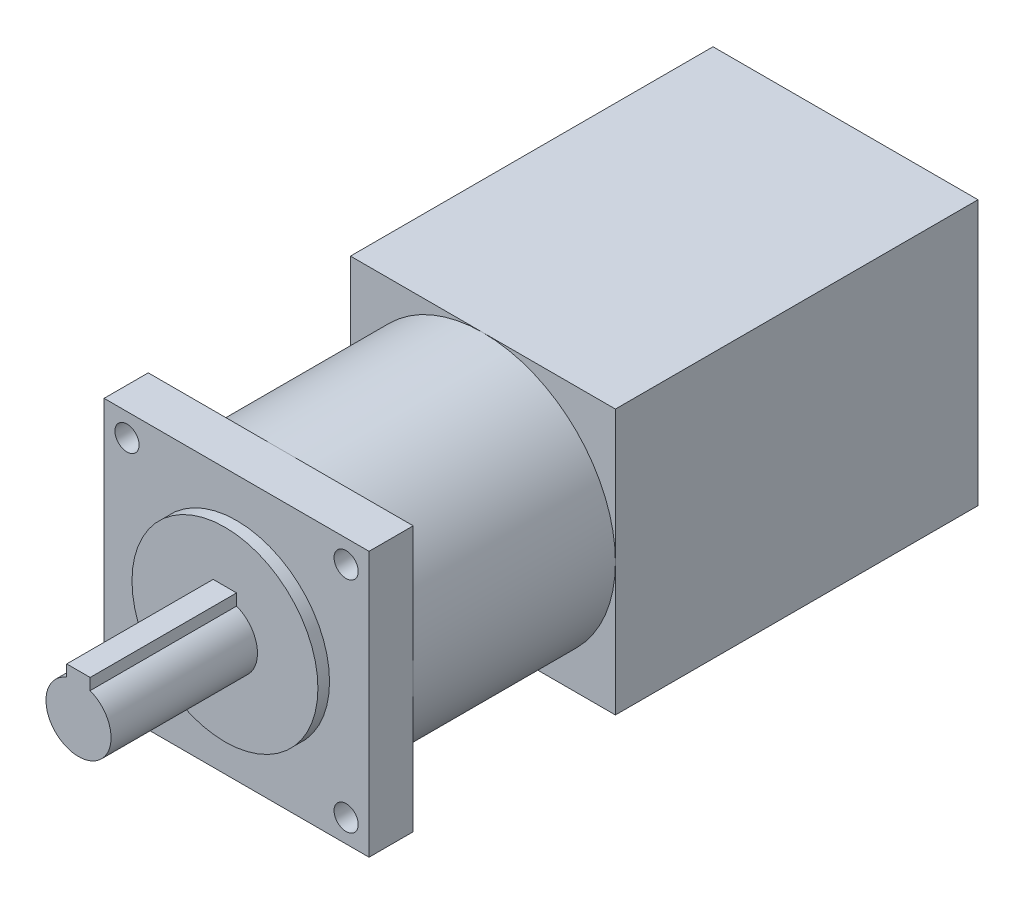
SolidWorks part; units mm, degrees
ref_plane "前视基准面" through (0, 0, 0) normal (0, 0, 1) x (1, 0, 0)
ref_plane "上视基准面" through (0, 0, 0) normal (0, 1, 0) x (1, 0, 0)
ref_plane "右视基准面" through (0, 0, 0) normal (1, 0, 0) x (0, 0, -1)
sketch "草图1" plane through (0, 0, 0) normal (0, 0, 1) x (1, 0, 0)
  line L1 (-28.5, 28.5) -> (28.5, 28.5)
  line L2 (-28.5, 28.5) -> (-28.5, -28.5)
  line L3 (-28.5, -28.5) -> (28.5, -28.5)
  line L4 (28.5, 28.5) -> (28.5, -28.5)
  line L5 (-28.5, 28.5) -> (28.5, -28.5) construction
  line L6 (-28.5, -28.5) -> (28.5, 28.5) construction
  point P0 (0, 0)
  dimension "D1" = 57
extrude "凸台-拉伸1" add sketch "草图1" along normal blind 78
sketch "草图2" plane through (0, 0, 78) normal (0, 0, 1) x (1, 0, 0)
  circle A0 centre (0, 0) radius 28.5
  dimension "D1" = 57
extrude "凸台-拉伸2" add sketch "草图2" along normal blind 53
sketch "草图3" plane through (0, 0, 131) normal (0, 0, 1) x (1, 0, 0)
  circle A0 centre (0, 0) radius 20
  dimension "D1" = 40
extrude "凸台-拉伸3" add sketch "草图3" along normal blind 2.5
sketch "草图4" plane through (0, 0, 133.5) normal (0, 0, 1) x (1, 0, 0)
  line L0 (0, 7) -> (0, 9) construction
  line L2 (0, 9) -> (2.5, 9)
  line L3 (0, 9) -> (-2.54, 9)
  line L4 (-2.54, 9) -> (-2.54, 6.5229)
  line L5 (2.5, 9) -> (2.5, 6.5383)
  circle A0 centre (0, 0) radius 7 construction
  arc A1 (-2.54, 6.5229) -> (2.5, 6.5383) centre (0, 0) ccw
  dimension "D1" = 14
extrude "凸台-拉伸4" add sketch "草图4" along normal blind 31.5
sketch "草图5" plane through (0, 0, 131) normal (0, 0, 1) x (1, 0, 0)
  circle A0 centre (0, 0) radius 17.5 construction
  circle A1 centre (0, -17.5) radius 2
  circle A2 centre (-17.5, 0) radius 2
  circle A3 centre (0, 17.5) radius 2
  circle A4 centre (17.5, 0) radius 2
  dimension "D1" = 4
extrude "切除-拉伸1" cut sketch "草图5" against normal blind 4
sketch "草图6" plane through (0, 0, 131) normal (0, 0, 1) x (1, 0, 0)
  line L0 (-23.57, 23.57) -> (23.57, 23.57) construction
  line L1 (28.5, -28.5) -> (-28.5, -28.5)
  line L2 (28.5, -28.5) -> (28.5, 28.5)
  line L3 (28.5, 28.5) -> (-28.5, 28.5)
  line L4 (-28.5, -28.5) -> (-28.5, 28.5)
  line L5 (28.5, -28.5) -> (-28.5, 28.5) construction
  line L6 (28.5, 28.5) -> (-28.5, -28.5) construction
  circle A0 centre (-23.57, 23.57) radius 2.6
  circle A1 centre (23.57, 23.57) radius 2.6
  circle A2 centre (23.57, -23.57) radius 2.6
  circle A3 centre (-23.57, -23.57) radius 2.6
  point P0 (0, 0)
  dimension "D3" = 4
  dimension "D1" = 57
  dimension "D2" = 47.14
extrude "凸台-拉伸5" add sketch "草图6" against normal blind 9.5
